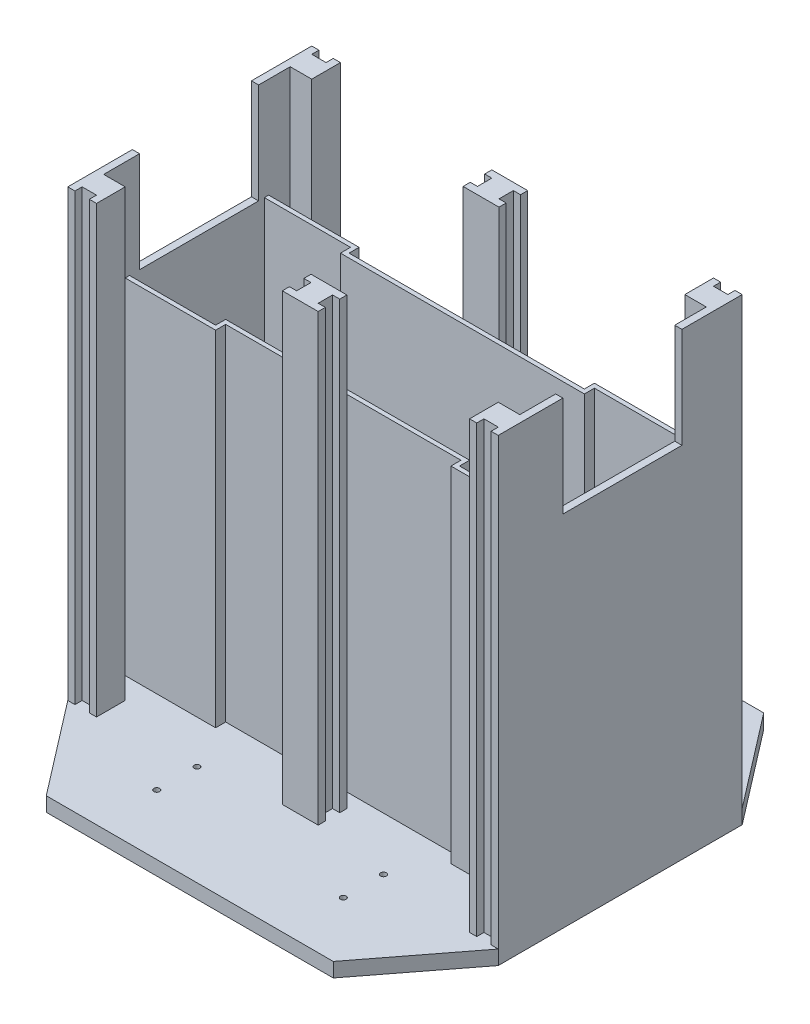
SolidWorks part; units mm, degrees
ref_plane "Front Plane" through (0, 0, 0) normal (0, 0, 1) x (1, 0, 0)
ref_plane "Top Plane" through (0, 0, 0) normal (0, 1, 0) x (1, 0, 0)
ref_plane "Right Plane" through (0, 0, 0) normal (1, 0, 0) x (0, 0, -1)
sketch "Sketch1" plane through (0, 0, 0) normal (0, 1, 0) x (1, 0, 0)
  line L0 (-100, 150) -> (-150, 85)
  line L1 (150, -150) -> (-150, -150) construction
  line L2 (150, -150) -> (150, 150) construction
  line L3 (150, 150) -> (-150, 150) construction
  line L4 (-150, -150) -> (-150, 150) construction
  line L5 (150, -150) -> (-150, 150) construction
  line L6 (150, 150) -> (-150, -150) construction
  line L7 (-150, -85) -> (-100, -150)
  line L8 (150, -85) -> (100, -150)
  line L9 (100, 150) -> (150, 85)
  line L10 (-100, 150) -> (100, 150)
  line L11 (150, 85) -> (150, -85)
  line L12 (100, -150) -> (-100, -150)
  line L13 (-150, -85) -> (-150, 85)
  line L15 (-140, -35) -> (-105, -35)
  line L16 (-140, -35) -> (-140, 35)
  line L17 (-140, 35) -> (-105, 35)
  line L18 (-105, -35) -> (-105, 35)
  line L19 (-140, -35) -> (-105, 35) construction
  line L20 (-140, 35) -> (-105, -35) construction
  line L21 (140, -35) -> (105, -35)
  line L22 (140, -35) -> (140, 35)
  line L23 (140, 35) -> (105, 35)
  line L24 (105, -35) -> (105, 35)
  line L25 (140, -35) -> (105, 35) construction
  line L26 (140, 35) -> (105, -35) construction
  point P0 (0, 0)
  point P14 (-122.5, 0)
  point P19 (122.5, 0)
  dimension "D1" = 300
  dimension "D2" = 300
  dimension "D3" = 170
  dimension "D4" = 200
  dimension "D5" = 35
  dimension "D6" = 35
  dimension "D7" = 105
  dimension "D8" = 105
  dimension "D9" = 70
extrude "Boss-Extrude1" add sketch "Sketch1" along normal blind 10
sketch "Sketch2" plane through (0, 10, 0) normal (0, 1, 0) x (1, 0, 0)
  line L0 (-150, 85) -> (-130, 85) construction
  line L1 (-130, 85) -> (-130, 65) construction
  line L2 (-130, 65) -> (-145, 65) construction
  line L3 (-145, 65) -> (-145, -65) construction
  line L4 (-145, -65) -> (-130, -65) construction
  line L5 (-130, -65) -> (-130, -85) construction
  line L6 (-130, -85) -> (-150, -85) construction
  line L7 (-150, -85) -> (-150, 85) construction
  line L8 (-145, -47) -> (-85, -47) construction
  line L9 (-85, -47) -> (-85, -40) construction
  line L10 (-85, -40) -> (85, -40) construction
  line L11 (85, -40) -> (85, -47) construction
  line L12 (85, -47) -> (145, -47) construction
  line L14 (150, -85) -> (130, -85) construction
  line L15 (130, -85) -> (130, -65) construction
  line L16 (130, -65) -> (145, -65) construction
  line L17 (145, -65) -> (145, 65) construction
  line L18 (145, 65) -> (130, 65) construction
  line L19 (130, 65) -> (130, 85) construction
  line L20 (130, 85) -> (150, 85) construction
  line L21 (150, 85) -> (150, -85) construction
  line L22 (0, 0) -> (0, -63) construction
  line L23 (12.5, -73) -> (-12.5, -73) construction
  line L24 (12.5, -73) -> (12.5, -53) construction
  line L25 (12.5, -53) -> (-12.5, -53) construction
  line L26 (-12.5, -73) -> (-12.5, -53) construction
  line L27 (12.5, -73) -> (-12.5, -53) construction
  line L28 (12.5, -53) -> (-12.5, -73) construction
  line L29 (-145, -50) -> (-82, -50) construction
  line L30 (-82, -50) -> (-82, -43) construction
  line L31 (-82, -43) -> (82, -43) construction
  line L32 (82, -43) -> (82, -50) construction
  line L33 (82, -50) -> (145, -50) construction
  line L34 (70, -114) -> (-70, -114)
  line L35 (70, -114) -> (70, -74)
  line L36 (70, -74) -> (-70, -74)
  line L37 (-70, -114) -> (-70, -74)
  line L38 (70, -114) -> (-70, -74) construction
  line L39 (70, -74) -> (-70, -114) construction
  line L40 (-22, -70) -> (-48, -70)
  line L41 (-22, -70) -> (-22, -56)
  line L42 (-22, -56) -> (-48, -56)
  line L43 (-48, -70) -> (-48, -56)
  line L44 (-22, -70) -> (-48, -56) construction
  line L45 (-22, -56) -> (-48, -70) construction
  point P3 (0, -40)
  point P28 (0, -63)
  point P41 (0, -94)
  point P47 (-35, -63)
  dimension "D1" = 20
  dimension "D2" = 20
  dimension "D3" = 5
  dimension "D4" = 40
  dimension "D5" = 60
  dimension "D6" = 25
  dimension "D7" = 20
  dimension "D9" = 15
  dimension "D10" = 10
  dimension "D11" = 140
  dimension "D12" = 40
  dimension "D13" = 14
  dimension "D14" = 18
  dimension "D15" = 26
  dimension "D16" = 35
  dimension "D8" = 3
sketch "Sketch4" plane through (0, 10, 0) normal (0, 1, 0) x (1, 0, 0)
  line L8 (-12.5, -53) -> (-12.5, -73) construction
  line L9 (-12.5, -73) -> (12.5, -73)
  line L10 (12.5, -73) -> (12.5, -53) construction
  line L11 (12.5, -53) -> (-12.5, -53)
  line L12 (-12.5, -53) -> (-12.5, -58)
  line L13 (-12.5, -58) -> (-7.5, -58)
  line L14 (-7.5, -58) -> (-7.5, -68)
  line L15 (-7.5, -68) -> (-12.5, -68)
  line L16 (-12.5, -68) -> (-12.5, -73)
  line L17 (12.5, -53) -> (12.5, -58)
  line L18 (12.5, -58) -> (7.5, -58)
  line L19 (7.5, -58) -> (7.5, -68)
  line L20 (7.5, -68) -> (12.5, -68)
  line L21 (12.5, -68) -> (12.5, -73)
  line L22 (-150, 85) -> (-150, -85)
  line L31 (-150, -85) -> (-145, -85)
  line L32 (-130, -85) -> (-150, -85) construction
  line L33 (-145, -85) -> (-145, -80)
  line L34 (-145, -80) -> (-135, -80)
  line L35 (-135, -80) -> (-135, -85)
  line L37 (-135, -85) -> (-130, -85)
  line L38 (-130, -85) -> (-130, -65)
  line L39 (-130, -65) -> (-145, -65)
  line L40 (-145, -65) -> (-145, 65)
  line L41 (-145, 65) -> (-130, 65)
  line L42 (-130, 65) -> (-130, 85)
  line L43 (-130, 85) -> (-135, 85)
  line L44 (-150, 85) -> (-130, 85) construction
  line L45 (-135, 85) -> (-135, 80)
  line L46 (-135, 80) -> (-145, 80)
  line L47 (-145, 80) -> (-145, 85)
  line L48 (-145, 85) -> (-150, 85)
  line L49 (0, -55) -> (0, 55) construction
  line L50 (145, 85) -> (150, 85)
  line L51 (145, 80) -> (145, 85)
  line L52 (135, 80) -> (145, 80)
  line L53 (135, 85) -> (135, 80)
  line L54 (130, 85) -> (135, 85)
  line L55 (130, 65) -> (130, 85)
  line L56 (145, 65) -> (130, 65)
  line L57 (145, -65) -> (145, 65)
  line L58 (130, -65) -> (145, -65)
  line L59 (130, -85) -> (130, -65)
  line L60 (135, -85) -> (130, -85)
  line L61 (135, -80) -> (135, -85)
  line L62 (145, -80) -> (135, -80)
  line L63 (145, -85) -> (145, -80)
  line L64 (150, -85) -> (145, -85)
  line L65 (150, 85) -> (150, -85)
  dimension "D1" = 10
  dimension "D2" = 15
  dimension "D3" = 5
  dimension "D4" = 5
  dimension "D5" = 5
  dimension "D6" = 10
  dimension "D7" = 5
  dimension "D8" = 5
extrude "Boss-Extrude3" add sketch "Sketch4" along normal blind 310
sketch "Sketch5" plane through (0, 10, 0) normal (0, 1, 0) x (1, 0, 0)
  line L0 (-145, -47) -> (-85, -47) construction
  line L1 (-145, -50) -> (-82, -50) construction
  line L2 (-85, -40) -> (85, -40) construction
  line L3 (-82, -43) -> (82, -43) construction
  line L4 (82, -50) -> (145, -50) construction
  line L5 (85, -47) -> (145, -47) construction
  line L6 (-145, -47) -> (-85, -47)
  line L7 (-145, -50) -> (-82, -50)
  line L8 (-85, -40) -> (85, -40)
  line L9 (-82, -43) -> (82, -43)
  line L10 (82, -50) -> (145, -50)
  line L11 (85, -47) -> (145, -47)
  line L12 (-145, -47) -> (-145, -50)
  line L13 (-85, -40) -> (-85, -47)
  line L14 (-82, -43) -> (-82, -50)
  line L15 (85, -40) -> (85, -47)
  line L16 (82, -43) -> (82, -50)
  line L17 (145, -47) -> (145, -50)
extrude "Boss-Extrude4" add sketch "Sketch5" along normal blind 240
sketch "Sketch6" plane through (0, 10, 0) normal (0, 1, 0) x (1, 0, 0)
  line L0 (70, -74) -> (-70, -74) construction
  line L1 (-70, -114) -> (-70, -74) construction
  line L2 (70, -114) -> (-70, -114) construction
  line L3 (0, -165) -> (0, 165) construction
  circle A0 centre (-65, -80) radius 2
  circle A1 centre (-65, -108) radius 2
  circle A2 centre (65, -108) radius 2
  circle A3 centre (65, -80) radius 2
  dimension "D2" = 5
  dimension "D3" = 4
  dimension "D4" = 4
  dimension "D5" = 6
  dimension "D6" = 5
  dimension "D1" = 6
extrude "Cut-Extrude1" cut sketch "Sketch6" against normal blind 280
mirror "Mirror1" about plane through (0, 0, 0) normal (0, 0, 1) of "Cut-Extrude1", "Boss-Extrude3", "Boss-Extrude4"
sketch "Sketch9" plane through (0, 0, 0) normal (1, 0, 0) x (0, 0, -1)
  line L0 (117.5, 0) -> (117.5, -4)
  line L1 (85, 0) -> (150, 0) construction
  line L2 (117.5, -4) -> (121.5, 0) construction
  line L3 (121.5, 0) -> (117.5, 0)
  arc A0 (117.5, -4) -> (121.5, 0) centre (117.5, 0) ccw
  dimension "D1" = 4
revolve "Revolve1" add sketch "Sketch9" angle 360 about L0
pattern_linear "LPattern1" count 2 spacing 100 along (-1, 0, 0) count 2 spacing 100 along (1, 0, 0) of "Revolve1"
mirror "Mirror2" about plane through (0, 0, 0) normal (0, 0, 1) of "LPattern1", "Revolve1"
sketch "Sketch10" plane through (-145, 0, 0) normal (1, 0, 0) x (0, 0, -1)
  line L0 (-40, 320) -> (-40, 250)
  line L1 (-85, 320) -> (85, 320) construction
  line L2 (43, 320) -> (43, 250)
  line L3 (-65, 320) -> (65, 320) construction
  line L4 (-40, 250) -> (43, 250)
  line L5 (-40, 320) -> (43, 320)
  point P10 (0, 0)
  point P11 (0, 0)
  point P13 (0, 0)
  dimension "D1" = 83
  dimension "D2" = 70
extrude "Cut-Extrude2" cut sketch "Sketch10" along normal up to surface (295 mm away) and the other way blind 10 up to face at (150, 110, 0)
sketch "Sketch11" plane through (0, 0, 43) normal (0, 0, 1) x (1, 0, 0)
  line L0 (-82, 250) -> (-82, 10) construction
  line L3 (-82, 140) -> (82, 140)
  line L4 (-82, 140) -> (-82, 135)
  line L5 (-82, 135) -> (82, 135)
  line L6 (82, 140) -> (82, 135)
  line L7 (82, 250) -> (82, 10) construction
  line L8 (-82, 250) -> (82, 250) construction
  dimension "D1" = 5
  dimension "D2" = 110
extrude "Boss-Extrude5" add sketch "Sketch11" against normal up to surface (86 mm away) up to face at (0, 130, -43)
